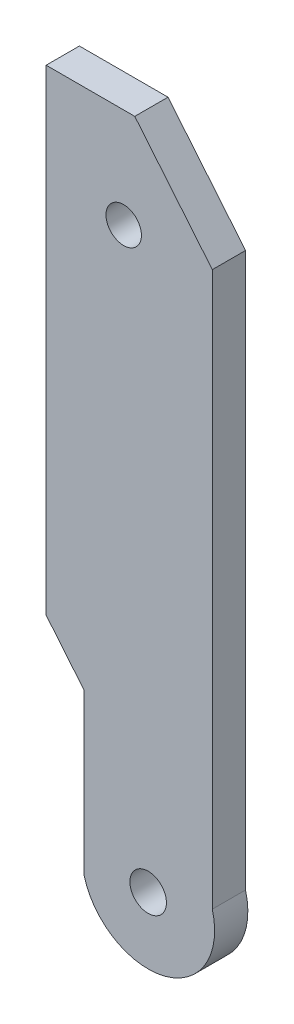
SolidWorks part; units mm, degrees
ref_plane "Front Plane" through (0, 0, 0) normal (0, 0, 1) x (1, 0, 0)
ref_plane "Top Plane" through (0, 0, 0) normal (0, 1, 0) x (1, 0, 0)
ref_plane "Right Plane" through (0, 0, 0) normal (1, 0, 0) x (0, 0, -1)
sketch "Sketch1" plane through (0, 0, 0) normal (0, 0, 1) x (1, 0, 0)
  line L6 (22.6503, 50.9256) -> (22.6503, 36.4403)
  line L7 (19.2309, 55.0705) -> (22.6503, 50.9256)
  line L8 (34.2309, 39.5851) -> (34.2309, 89.5851)
  line L9 (34.2309, 89.5851) -> (27.2309, 98.0704)
  line L10 (27.2309, 98.0704) -> (19.2309, 98.0704)
  line L11 (19.2309, 98.0704) -> (19.2309, 55.0705)
  arc A0 (34.2309, 39.5851) -> (22.6503, 36.4403) centre (28.4406, 38.0127) cw
  circle A1 centre (28.4406, 38.0127) radius 1.65 construction
  circle A2 centre (28.4406, 38.0127) radius 1.65
  circle A3 centre (26.2309, 89.0704) radius 1.6 construction
  circle A4 centre (26.2309, 89.0704) radius 1.6
extrude "Boss-Extrude1" add sketch "Sketch1" along normal blind 3 contours A0 L8 L9 L10 L11 L7 L6
